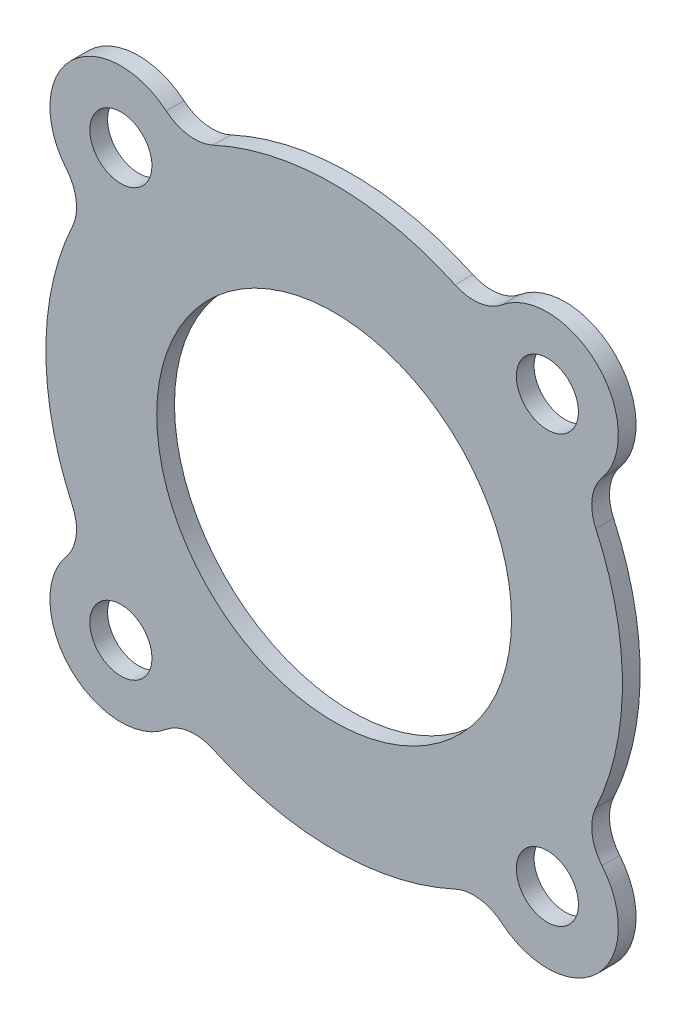
SolidWorks part; units mm, degrees
ref_plane "前视基准面" through (0, 0, 0) normal (0, 0, 1) x (1, 0, 0)
ref_plane "上视基准面" through (0, 0, 0) normal (0, 1, 0) x (1, 0, 0)
ref_plane "右视基准面" through (0, 0, 0) normal (1, 0, 0) x (0, 0, -1)
sketch "草图1" plane through (0, 0, 0) normal (0, 0, 1) x (1, 0, 0)
  circle A0 centre (0, 0) radius 20
  circle A1 centre (0, 0) radius 32.5
  point P4 (0, 0)
  point P5 (0, 0)
  dimension "D1" = 40
  dimension "D2" = 65
extrude "凸台-拉伸1" add sketch "草图1" along normal blind 2
sketch "草图2" plane through (0, 0, 2) normal (0, 0, 1) x (1, 0, 0)
  line L0 (0, 0) -> (12.4644, 0) construction
  line L1 (12.4644, 0) -> (0, 0) construction
  line L2 (0, 0) -> (24.0416, 24.0416) construction
  circle A0 centre (24.0416, 24.0416) radius 8
  dimension "D3" = 16
  dimension "D1" = 45
  dimension "D2" = 34
extrude "凸台-拉伸2" add sketch "草图2" against normal blind 2
sketch "草图3" plane through (0, 0, 2) normal (0, 0, 1) x (1, 0, 0)
  circle A0 centre (24.0416, 24.0416) radius 3.5
  dimension "D1" = 7
extrude "切除-拉伸1" cut sketch "草图3" against normal blind 2
fillet "圆角1" radius 5 2 edges at (27.7333, 16.9444, 1) (16.9444, 27.7333, 1)
pattern_circular "阵列(圆周)1" count 4 over 360 about axis through (0, 0, 0) along (0, 0, 1) of "圆角1", "切除-拉伸1", "凸台-拉伸2"
